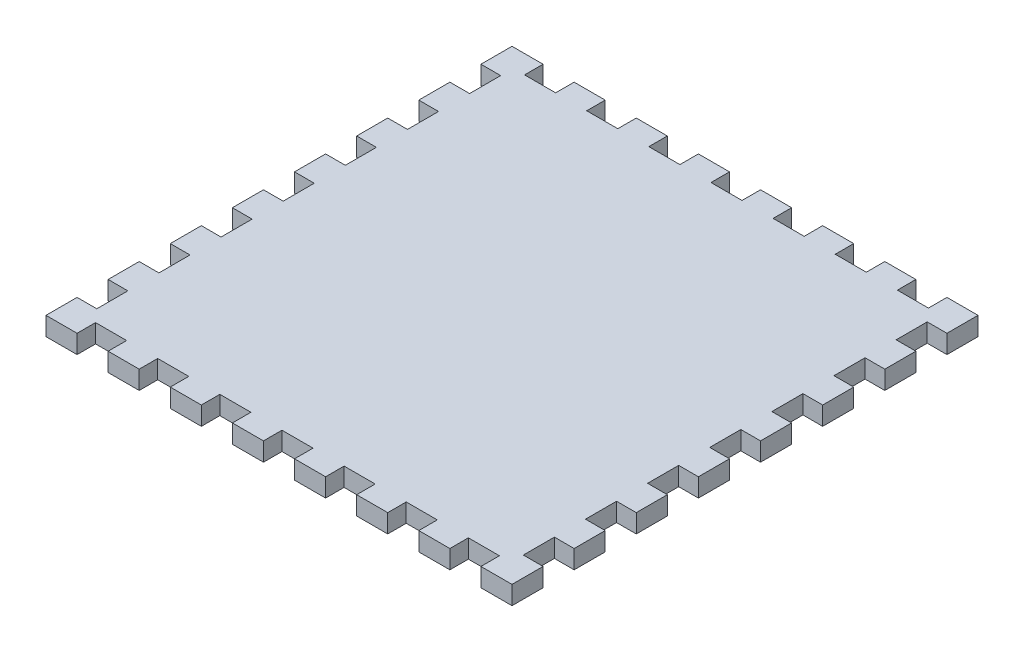
SolidWorks part; units mm, degrees
material "Acrylic (Medium-high impact)"
ref_plane "Front Plane" through (0, 0, 0) normal (0, 0, 1) x (1, 0, 0)
ref_plane "Top Plane" through (0, 0, 0) normal (0, 1, 0) x (1, 0, 0)
ref_plane "Right Plane" through (0, 0, 0) normal (1, 0, 0) x (0, 0, -1)
sketch "Sketch1" plane through (0, 0, 0) normal (0, 1, 0) x (1, 0, 0)
  line L1 (-40, -40) -> (40, -40)
  line L2 (-40, -40) -> (-40, 40)
  line L3 (-40, 40) -> (40, 40)
  line L4 (40, -40) -> (40, 40)
  line L5 (-40, -40) -> (40, 40) construction
  line L6 (-40, 40) -> (40, -40) construction
  point P0 (0, 0)
  dimension "D1" = 80
  dimension "D2" = 80
extrude "Boss-Extrude1" add sketch "Sketch1" along normal blind 3.175
sketch "Sketch3" plane through (0, 3.175, 0) normal (0, 1, 0) x (1, 0, 0)
  line L0 (0, 0) -> (50000, 0) construction
  line L1 (-40, -40) -> (-34.6667, -40)
  line L2 (34.6667, 40) -> (40, 40)
  line L3 (-34.6667, -40) -> (-34.6667, -36.825)
  line L4 (-34.6667, -36.825) -> (-29.3333, -36.825)
  line L5 (-29.3333, -36.825) -> (-29.3333, -40)
  line L6 (-29.3333, -40) -> (-24, -40)
  line L7 (-24, -40) -> (-24, -36.825)
  line L8 (-24, -36.825) -> (-18.6667, -36.825)
  line L9 (-18.6667, -36.825) -> (-18.6667, -40)
  line L10 (-18.6667, -40) -> (-13.3333, -40)
  line L11 (-13.3333, -40) -> (-13.3333, -36.825)
  line L12 (-13.3333, -36.825) -> (-8, -36.825)
  line L13 (-8, -36.825) -> (-8, -40)
  line L14 (-8, -40) -> (-2.6667, -40)
  line L15 (-2.6667, -40) -> (-2.6667, -36.825)
  line L16 (-2.6667, -36.825) -> (2.6667, -36.825)
  line L17 (2.6667, -36.825) -> (2.6667, -40)
  line L18 (2.6667, -40) -> (8, -40)
  line L19 (8, -40) -> (8, -36.825)
  line L20 (8, -36.825) -> (13.3333, -36.825)
  line L21 (13.3333, -36.825) -> (13.3333, -40)
  line L22 (13.3333, -40) -> (18.6667, -40)
  line L23 (18.6667, -40) -> (18.6667, -36.825)
  line L24 (18.6667, -36.825) -> (24, -36.825)
  line L25 (24, -36.825) -> (24, -40)
  line L26 (24, -40) -> (29.3333, -40)
  line L27 (29.3333, -40) -> (29.3333, -36.825)
  line L28 (29.3333, -36.825) -> (34.6667, -36.825)
  line L29 (34.6667, -36.825) -> (34.6667, -40)
  line L30 (34.6667, -40) -> (40, -40)
  line L31 (34.6667, 36.825) -> (34.6667, 40)
  line L32 (29.3333, 36.825) -> (34.6667, 36.825)
  line L33 (29.3333, 40) -> (29.3333, 36.825)
  line L34 (24, 40) -> (29.3333, 40)
  line L35 (24, 36.825) -> (24, 40)
  line L36 (18.6667, 36.825) -> (24, 36.825)
  line L37 (18.6667, 40) -> (18.6667, 36.825)
  line L38 (13.3333, 40) -> (18.6667, 40)
  line L39 (13.3333, 36.825) -> (13.3333, 40)
  line L40 (8, 36.825) -> (13.3333, 36.825)
  line L41 (8, 40) -> (8, 36.825)
  line L42 (2.6667, 40) -> (8, 40)
  line L43 (2.6667, 36.825) -> (2.6667, 40)
  line L44 (-2.6667, 36.825) -> (2.6667, 36.825)
  line L45 (-2.6667, 40) -> (-2.6667, 36.825)
  line L46 (-8, 40) -> (-2.6667, 40)
  line L47 (-8, 36.825) -> (-8, 40)
  line L48 (-13.3333, 36.825) -> (-8, 36.825)
  line L49 (-13.3333, 40) -> (-13.3333, 36.825)
  line L50 (-18.6667, 40) -> (-13.3333, 40)
  line L51 (-18.6667, 36.825) -> (-18.6667, 40)
  line L52 (-24, 36.825) -> (-18.6667, 36.825)
  line L53 (-24, 40) -> (-24, 36.825)
  line L54 (-29.3333, 40) -> (-24, 40)
  line L55 (-29.3333, 36.825) -> (-29.3333, 40)
  line L56 (-34.6667, 36.825) -> (-29.3333, 36.825)
  line L57 (-34.6667, 40) -> (-34.6667, 36.825)
  line L58 (-40, 40) -> (-34.6667, 40)
  line L59 (0, 0) -> (0, 50000) construction
  line L60 (40, 40) -> (40, 34.6667)
  line L61 (40, -40) -> (40, 40) construction
  line L62 (40, 34.6667) -> (36.6133, 34.6667)
  line L63 (36.6133, 34.6667) -> (36.6133, 29.3333)
  line L64 (36.6133, 29.3333) -> (40, 29.3333)
  line L65 (40, 29.3333) -> (40, 24)
  line L66 (40, 24) -> (36.6133, 24)
  line L67 (36.6133, 24) -> (36.6133, 18.6667)
  line L68 (36.6133, 18.6667) -> (40, 18.6667)
  line L69 (40, 18.6667) -> (40, 13.3333)
  line L70 (40, 13.3333) -> (36.6133, 13.3333)
  line L71 (36.6133, 13.3333) -> (36.6133, 8)
  line L72 (36.6133, 8) -> (40, 8)
  line L73 (40, 8) -> (40, 2.6667)
  line L74 (40, 2.6667) -> (36.6133, 2.6667)
  line L75 (36.6133, 2.6667) -> (36.6133, -2.6667)
  line L76 (36.6133, -2.6667) -> (40, -2.6667)
  line L77 (40, -2.6667) -> (40, -8)
  line L78 (40, -8) -> (36.6133, -8)
  line L79 (36.6133, -8) -> (36.6133, -13.3333)
  line L80 (36.6133, -13.3333) -> (40, -13.3333)
  line L81 (40, -13.3333) -> (40, -18.6667)
  line L82 (40, -18.6667) -> (36.6133, -18.6667)
  line L83 (36.6133, -18.6667) -> (36.6133, -24)
  line L84 (36.6133, -24) -> (40, -24)
  line L85 (40, -24) -> (40, -29.3333)
  line L86 (40, -29.3333) -> (36.6133, -29.3333)
  line L87 (36.6133, -29.3333) -> (36.6133, -34.6667)
  line L88 (36.6133, -34.6667) -> (40, -34.6667)
  line L89 (40, -34.6667) -> (40, -40)
  line L90 (0, 0) -> (-50000, 0) construction
  line L91 (-40, -34.6667) -> (-40, -40)
  line L92 (-36.6133, -34.6667) -> (-40, -34.6667)
  line L93 (-40, -29.3333) -> (-36.6133, -29.3333)
  line L94 (-40, -24) -> (-40, -29.3333)
  line L95 (-36.6133, -24) -> (-40, -24)
  line L96 (-40, -18.6667) -> (-36.6133, -18.6667)
  line L97 (-40, -13.3333) -> (-40, -18.6667)
  line L98 (-36.6133, -13.3333) -> (-40, -13.3333)
  line L99 (-40, -8) -> (-36.6133, -8)
  line L100 (-40, -2.6667) -> (-40, -8)
  line L101 (-36.6133, -2.6667) -> (-40, -2.6667)
  line L102 (-40, 2.6667) -> (-36.6133, 2.6667)
  line L103 (-40, 8) -> (-40, 2.6667)
  line L104 (-36.6133, 8) -> (-40, 8)
  line L105 (-40, 13.3333) -> (-36.6133, 13.3333)
  line L106 (-40, 18.6667) -> (-40, 13.3333)
  line L107 (-36.6133, 18.6667) -> (-40, 18.6667)
  line L108 (-40, 24) -> (-36.6133, 24)
  line L109 (-40, 29.3333) -> (-40, 24)
  line L110 (-36.6133, 29.3333) -> (-40, 29.3333)
  line L111 (-40, 34.6667) -> (-36.6133, 34.6667)
  line L112 (-40, 40) -> (-40, 34.6667)
  line L114 (-36.6133, -29.3333) -> (-36.6133, -34.6667)
  line L115 (-36.6133, -18.6667) -> (-36.6133, -24)
  line L116 (-36.6133, -8) -> (-36.6133, -13.3333)
  line L117 (-36.6133, 2.6667) -> (-36.6133, -2.6667)
  line L118 (-36.6133, 13.3333) -> (-36.6133, 8)
  line L119 (-36.6133, 24) -> (-36.6133, 18.6667)
  line L120 (-36.6133, 34.6667) -> (-36.6133, 29.3333)
  dimension "D1" = 5.3333
  dimension "D2" = 7
  dimension "D3" = 5.3333
extrude "Cut-Extrude1" cut sketch "Sketch3" against normal through all flip side to cut
